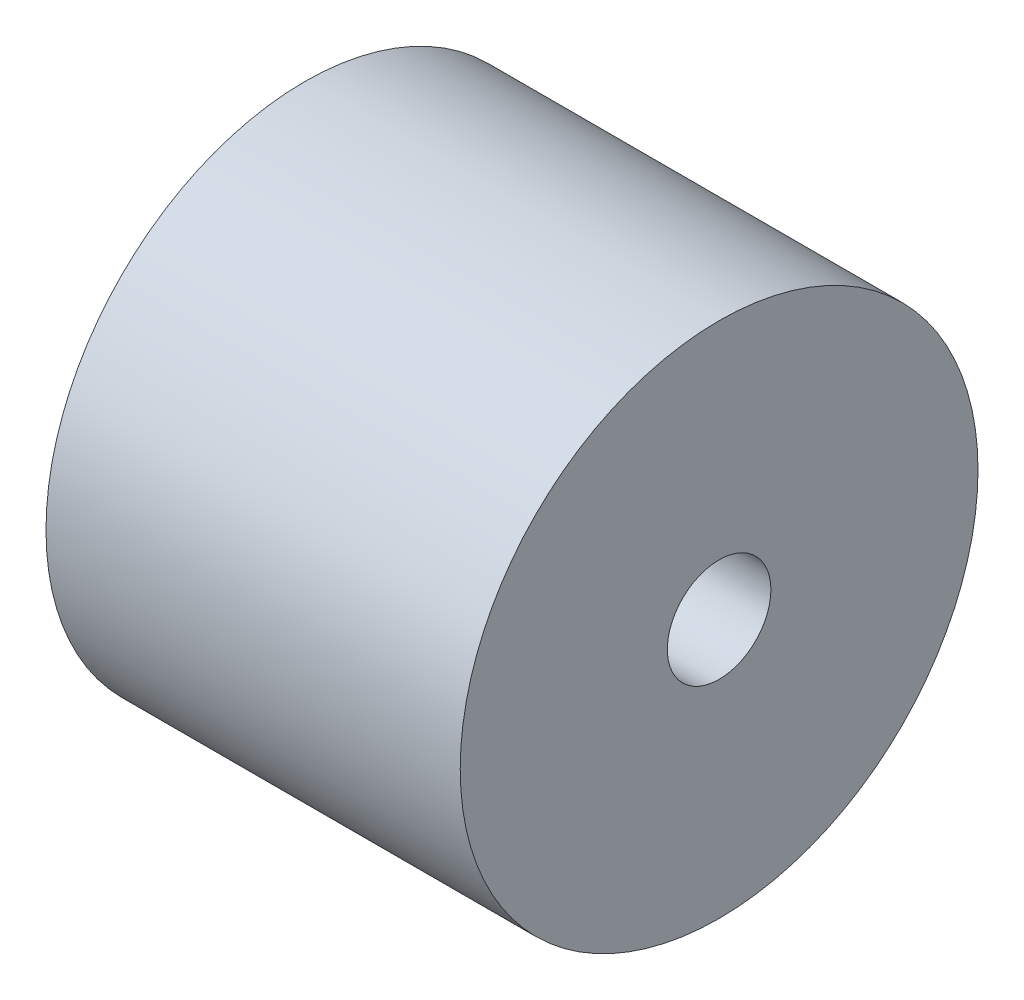
SolidWorks part; units mm, degrees
ref_plane "前视基准面" through (0, 0, 0) normal (0, 0, 1) x (1, 0, 0)
ref_plane "上视基准面" through (0, 0, 0) normal (0, 1, 0) x (1, 0, 0)
ref_plane "右视基准面" through (0, 0, 0) normal (1, 0, 0) x (0, 0, -1)
other "Configuration Table"
sketch "草图1" plane through (0, 0, 0) normal (1, 0, 0) x (0, 0, -1)
  circle A0 centre (0, 0) radius 10
  dimension "D1" = 20
extrude "凸台-拉伸1" add sketch "草图1" along normal blind 16
sketch "草图2" plane through (16, 0, 0) normal (1, 0, 0) x (0, 0, -1)
  circle A0 centre (0, 0) radius 2
  dimension "D1" = 4
extrude "切除-拉伸1" cut sketch "草图2" against normal blind 10
